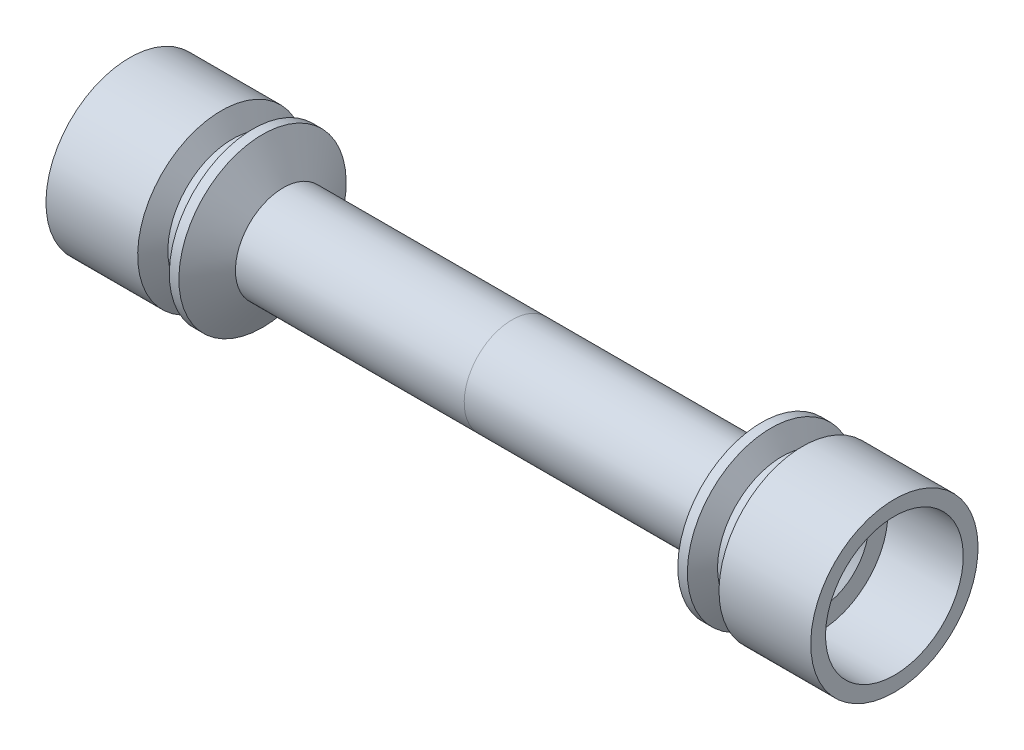
SolidWorks part; units mm, degrees
ref_plane "Front Plane" through (0, 0, 0) normal (0, 0, 1) x (1, 0, 0)
ref_plane "Top Plane" through (0, 0, 0) normal (0, 1, 0) x (1, 0, 0)
ref_plane "Right Plane" through (0, 0, 0) normal (1, 0, 0) x (0, 0, -1)
sketch "Sketch2" plane through (0, 0, 0) normal (0, 0, 1) x (1, 0, 0)
  line L0 (0, 0) -> (0, 28.4375) construction
  line L1 (-25.4, 4.575) -> (-20.4, 4.575) construction
  line L2 (-25.4, 4.575) -> (-25.4, -4.575) construction
  line L3 (-25.4, -4.575) -> (-20.4, -4.575) construction
  line L4 (-20.4, 4.575) -> (-20.4, -4.575) construction
  line L5 (-25.4, 4.575) -> (-20.4, -4.575) construction
  line L6 (-25.4, -4.575) -> (-20.4, 4.575) construction
  line L7 (20.4, 4.5) -> (43.1832, 4.5) construction
  line L8 (20.4, 4.5) -> (20.4, -4.5) construction
  line L9 (20.4, -4.5) -> (43.1832, -4.5) construction
  line L10 (43.1832, 4.5) -> (43.1832, -4.5) construction
  line L11 (20.4, 4.5) -> (43.1832, -4.5) construction
  line L12 (20.4, -4.5) -> (43.1832, 4.5) construction
  line L13 (-25.4, 0) -> (43.1832, 0) construction
  line L14 (-25.4, 5.5562) -> (-19.307, 5.5562)
  line L21 (-15.1957, 3.175) -> (0, 3.175)
  line L22 (-25.4, 5.5562) -> (-25.4, 4.575)
  line L23 (-25.4, 4.575) -> (-20.4, 4.575)
  line L24 (-20.4, 4.575) -> (-20.4, 0)
  line L25 (-20.4, 0) -> (0, 0)
  line L26 (0, 0) -> (0, 3.175)
  line L27 (-33.5594, -5.5562) -> (-33.5594, 5.5562) construction
  line L28 (-19.307, 5.5562) -> (-18.5737, 4.2862)
  line L29 (-18.5737, 4.2862) -> (-17.9387, 4.2862)
  line L30 (-25.4, 5.5562) -> (25.4, 5.5562) construction
  line L31 (0, 1.6) -> (-12.5, 1.6)
  line L32 (-12.5, 1.6) -> (-14.1, 0)
  line L33 (-12.5, 1.6) -> (-12.5, -1.6) construction
  line L34 (-12.5, 1.6) -> (12.5, 1.6) construction
  line L35 (-20.4, 1.7145) -> (-15.575, 1.7145)
  line L36 (-15.575, 1.7145) -> (-15.575, 0)
  line L37 (-20.4, 3.305) -> (-19.892, 2.797)
  line L38 (-15.575, 1.7145) -> (-28.575, 1.7145) construction
  line L39 (-15.575, 1.7145) -> (-15.575, -1.7145) construction
  line L40 (-15.575, -1.7145) -> (-28.575, -1.7145) construction
  line L41 (-28.575, 1.7145) -> (-28.575, -1.7145) construction
  line L42 (-19.892, 2.797) -> (-19.892, 0)
  line L46 (-17.9387, 4.2862) -> (-17.2055, 5.5562)
  line L47 (-17.2055, 5.5562) -> (-16.5705, 5.5562)
  line L48 (-16.5705, 5.5562) -> (-15.1957, 3.175)
  line L49 (-18.2562, 4.2862) -> (-18.2562, 6.3987) construction
  line L50 (-18.2562, 6.3987) -> (18.2562, 6.3987) construction
  point P0 (-22.9, 0)
  point P5 (31.7916, 0)
  point P27 (-33.5594, 0)
  point P28 (-18.8314, 6.3987)
  point P29 (-12.5, 0)
  point P33 (0, 6.3987)
  point P35 (-18.6093, 5.5562)
  point P36 (0, 1.6)
  point P48 (-15.575, 0)
  point P51 (0, 5.5562)
  point P52 (-20.4916, 6.5757)
  dimension "D3" = 3.175
  dimension "D4" = 11.1125
  dimension "D5" = 9.15
  dimension "D6" = 60
  dimension "D7" = 0.635
  dimension "D8" = 60
  dimension "D9" = 36.5125
  dimension "D10" = 1.27
  dimension "D11" = 50.8
  dimension "D12" = 0.635
  dimension "D13" = 45
  dimension "D14" = 25
  dimension "D15" = 3.2
  dimension "D16" = 3.429
  dimension "D17" = 3.175
  dimension "D18" = 1.27
  dimension "D19" = 0.508
  dimension "D20" = 45
  dimension "D21" = 13
  dimension "D22" = 5
revolve "Revolve1" add sketch "Sketch2" angle 360 about L13
mirror "Mirror1" about plane through (0, 0, 0) normal (1, 0, 0) of bodies 101
chamfer "Chamfer1" distance 0.508 angle 45 1 edges at (-25.4, -4.575, 0)
